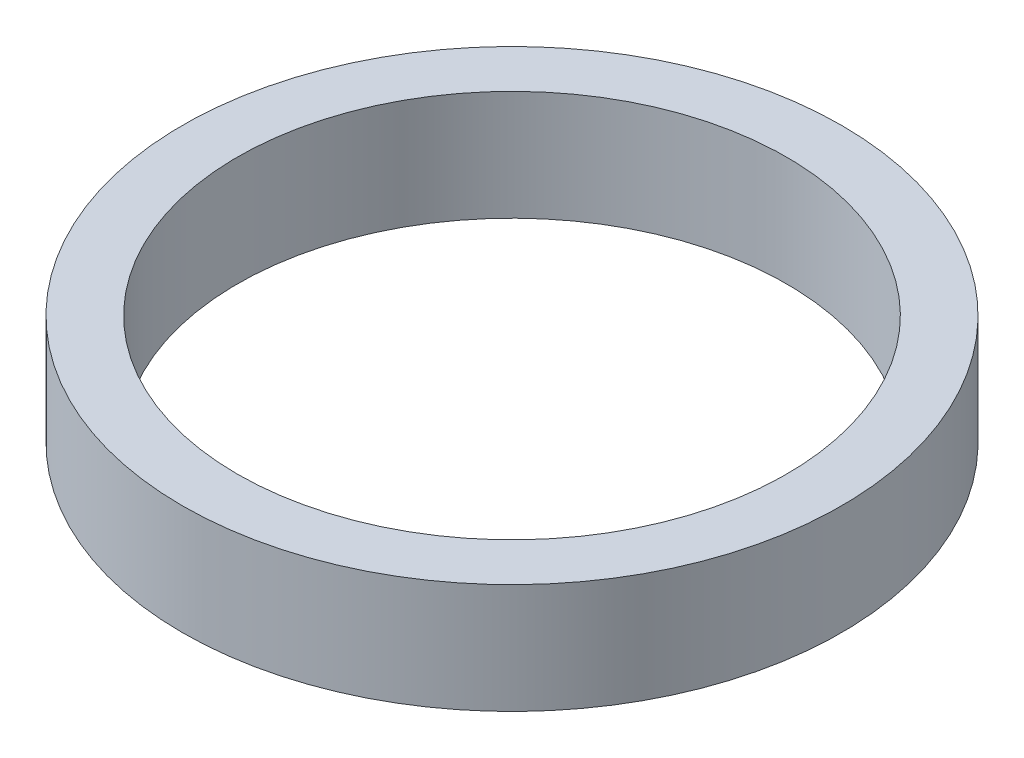
SolidWorks part; units mm, degrees
ref_plane "Front Plane" through (0, 0, 0) normal (0, 0, 1) x (1, 0, 0)
ref_plane "Top Plane" through (0, 0, 0) normal (0, 1, 0) x (1, 0, 0)
ref_plane "Right Plane" through (0, 0, 0) normal (1, 0, 0) x (0, 0, -1)
sketch "Sketch1" plane through (0, 0, 0) normal (0, 1, 0) x (1, 0, 0)
  circle A1 centre (0, 0) radius 15.24
extrude "Boss-Extrude1" add sketch "Sketch1" along normal blind 5.08
sketch "Sketch2" plane through (0, 5.08, 0) normal (0, 1, 0) x (1, 0, 0)
  circle A0 centre (0, 0) radius 12.7
extrude "Cut-Extrude1" cut sketch "Sketch2" against normal blind 5.08
